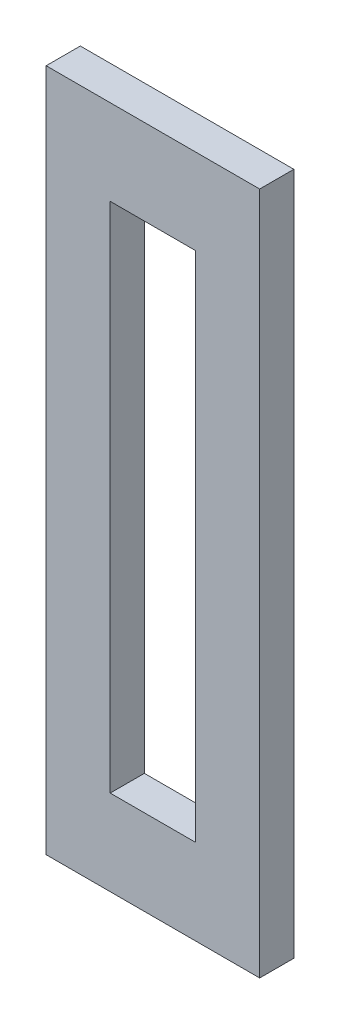
SolidWorks part; units mm, degrees
ref_plane "Front Plane" through (0, 0, 0) normal (0, 0, 1) x (1, 0, 0)
ref_plane "Top Plane" through (0, 0, 0) normal (0, 1, 0) x (1, 0, 0)
ref_plane "Right Plane" through (0, 0, 0) normal (1, 0, 0) x (0, 0, -1)
sketch "Sketch1" plane through (0, 0, 0) normal (0, 0, 1) x (1, 0, 0)
  line L1 (-12.5, -40) -> (12.5, -40)
  line L2 (-12.5, -40) -> (-12.5, 40)
  line L3 (-12.5, 40) -> (12.5, 40)
  line L4 (12.5, -40) -> (12.5, 40)
  line L5 (-12.5, -40) -> (12.5, 40) construction
  line L6 (-12.5, 40) -> (12.5, -40) construction
  point P0 (0, 0)
  dimension "D1" = 25
  dimension "D2" = 80
extrude "Boss-Extrude1" add sketch "Sketch1" along normal blind 4
sketch "Sketch2" plane through (0, 0, 0) normal (0, 0, 1) x (1, 0, 0)
  line L1 (-5, -30) -> (5, -30)
  line L2 (-5, -30) -> (-5, 30)
  line L3 (-5, 30) -> (5, 30)
  line L4 (5, -30) -> (5, 30)
  line L5 (-5, -30) -> (5, 30) construction
  line L6 (-5, 30) -> (5, -30) construction
  point P0 (0, 0)
  dimension "D1" = 60
  dimension "D2" = 10
extrude "Cut-Extrude1" cut sketch "Sketch2" along normal blind 10
